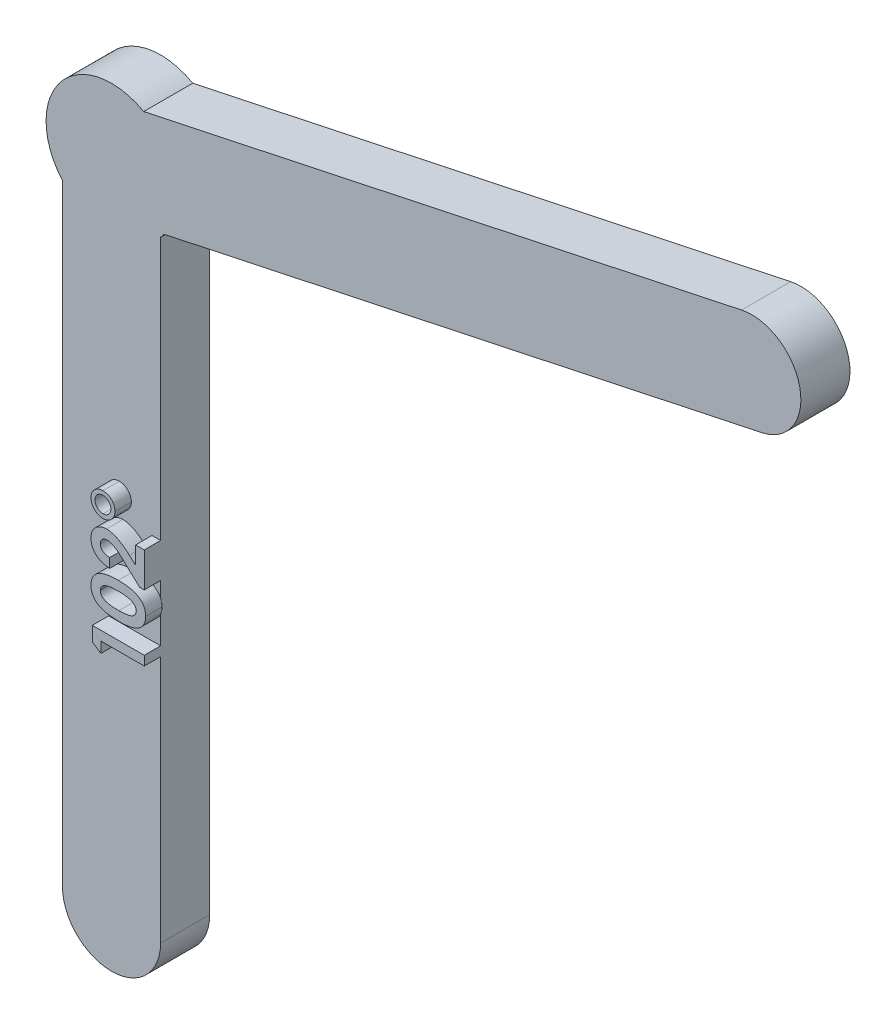
SolidWorks part; units mm, degrees
ref_plane "Front Plane" through (0, 0, 0) normal (0, 0, 1) x (1, 0, 0)
ref_plane "Top Plane" through (0, 0, 0) normal (0, 1, 0) x (1, 0, 0)
ref_plane "Right Plane" through (0, 0, 0) normal (1, 0, 0) x (0, 0, -1)
sketch "Sketch2" plane through (0, 0, 0) normal (0, 0, 1) x (1, 0, 0)
  line L0 (0, 0) -> (0, -40) construction
  line L1 (0, 0) -> (39.1259, 8.3165) construction
  line L2 (38.5022, 11.2509) -> (39.7496, 5.382) construction
  line L3 (-3, -40) -> (3, -40) construction
  line L4 (-3, -40) -> (-3, -2.6458)
  line L5 (3, -40) -> (3, -2.6458)
  line L6 (38.5022, 11.2509) -> (1.9642, 3.4845)
  line L7 (39.7496, 5.382) -> (3.2117, -2.3844)
  arc A0 (1.9642, 3.4845) -> (-3, -2.6458) centre (0, 0) ccw
  arc A1 (-3, -40) -> (3, -40) centre (0, -40) ccw
  arc A2 (38.5022, 11.2509) -> (39.7496, 5.382) centre (39.1259, 8.3165) cw
  arc A3 (3, -2.6458) -> (3.2117, -2.3844) centre (0, 0) ccw
  point P12 (39.1259, 8.3165)
  dimension "D3" = 3
  dimension "D4" = 8
  dimension "D1" = 40
  dimension "D2" = 102
extrude "Boss-Extrude1" add sketch "Sketch2" along normal blind 3
sketch "Sketch3" plane through (0, 0, 3) normal (0, 0, 1) x (1, 0, 0)
  text T0 "<b>102°</b>"
extrude "Boss-Extrude2" add sketch "Sketch3" along normal blind 1
